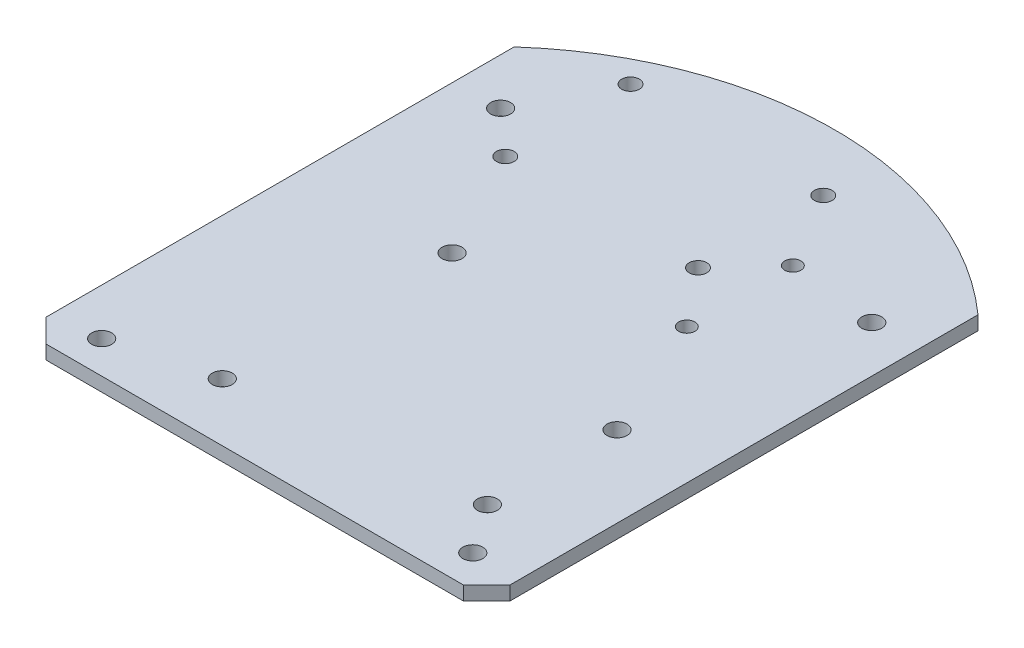
SolidWorks part; units mm, degrees
ref_plane "Front Plane" through (0, 0, 0) normal (0, 0, 1) x (1, 0, 0)
ref_plane "Top Plane" through (0, 0, 0) normal (0, 1, 0) x (1, 0, 0)
ref_plane "Right Plane" through (0, 0, 0) normal (1, 0, 0) x (0, 0, -1)
sketch "Sketch1" plane through (0, 0, 0) normal (0, 1, 0) x (1, 0, 0)
  line L1 (50, -50) -> (-50, -50)
  line L2 (50, -50) -> (50, 50)
  line L3 (50, 50) -> (-50, 50)
  line L4 (-50, -50) -> (-50, 50)
  line L5 (50, -50) -> (-50, 50) construction
  line L6 (50, 50) -> (-50, -50) construction
  point P0 (0, 0)
  dimension "D1" = 100
  dimension "D2" = 100
extrude "Boss-Extrude1" add sketch "Sketch1" along normal blind 3
sketch "Sketch2" plane through (0, 3, 0) normal (0, 1, 0) x (1, 0, 0)
  line L0 (0, -55) -> (0, 55) construction
  line L1 (-55, 0) -> (55, 0) construction
  circle A0 centre (-40, 43) radius 1.75
  dimension "D1" = 3.5
  dimension "D2" = 40
  dimension "D3" = 43
extrude "Cut-Extrude1" cut sketch "Sketch2" against normal through all
mirror "Mirror1" about plane through (0, 0, 0) normal (1, 0, 0) of "Cut-Extrude1"
mirror "Mirror2" about plane through (0, 0, 0) normal (0, 0, 1) of "Mirror1", "Cut-Extrude1"
chamfer "Chamfer1" distance 5 angle 45 4 edges at (-50, 1.5, 50) (50, 1.5, 50) (50, 1.5, -50) (-50, 1.5, -50)
sketch "Sketch6" plane through (0, 3, 0) normal (0, 1, 0) x (1, 0, 0)
  circle A4 centre (-18.23, 10.76) radius 1.75
  circle A5 centre (-19.5, -37.5) radius 1.75
  circle A6 centre (32.57, -32.42) radius 1.75
  circle A7 centre (32.57, -4.48) radius 1.75
  dimension "D1" = 3.5
  dimension "D2" = 3.5
  dimension "D3" = 3.5
  dimension "D4" = 3.5
sketch "Sketch7" plane through (0, 3, 0) normal (0, 1, 0) x (1, 0, 0)
  line L0 (-50, 45) -> (-50, 55.9017)
  line L1 (50, 45) -> (50, 55.9017)
  line L2 (45, 50) -> (-45, 50) construction
  arc A0 (-50, 55.9017) -> (50, 55.9017) centre (0, 0) cw
  dimension "D1" = 75
  dimension "D2" = 100
  dimension "D3" = 5.9017
sketch "Sketch8" plane through (0, 3, 0) normal (0, 1, 0) x (1, 0, 0)
  circle A0 centre (6.5, 61.5) radius 1.75 construction
  circle A1 centre (-30.5, 61.5) radius 1.75 construction
  circle A2 centre (6.5, 61.5) radius 1.75
  circle A3 centre (-30.5, 61.5) radius 1.75
  circle A5 centre (-30.5, 24.5) radius 1.75
  circle A6 centre (-30.5, 24.5) radius 1.75
  circle A7 centre (-30.5, 61.5) radius 1.75
  circle A8 centre (-30.5, 61.5) radius 1.75
  circle A9 centre (6.5, 61.5) radius 1.75
  circle A10 centre (6.5, 61.5) radius 1.75
  circle A11 centre (6.5, 24.5) radius 1.75
  circle A12 centre (6.5, 24.5) radius 1.75
  dimension "D1" = 0
  dimension "D2" = 0
  dimension "D3" = 0
  dimension "D4" = 0
sketch "Sketch9" plane through (0, 3, 0) normal (0, 1, 0) x (1, 0, 0)
  line L0 (50, 45) -> (50, 55.9017) construction
  line L1 (-50, 45) -> (-50, 55.9017) construction
  line L2 (50, 45) -> (50, 55.9017)
  line L3 (-50, 45) -> (-50, 55.9017)
  line L12 (-50, 45) -> (-50, -45)
  line L13 (-50, -45) -> (-45, -50)
  line L14 (-45, -50) -> (45, -50)
  line L15 (45, -50) -> (50, -45)
  line L16 (50, -45) -> (50, 45)
  line L17 (50, 45) -> (45, 50)
  line L18 (45, 50) -> (-45, 50)
  line L19 (-45, 50) -> (-50, 45)
  line L20 (-50, 45) -> (-50, -45)
  line L21 (-50, -45) -> (-45, -50)
  line L22 (-45, -50) -> (45, -50)
  line L23 (45, -50) -> (50, -45)
  line L24 (50, -45) -> (50, 45)
  line L25 (50, 45) -> (45, 50)
  line L26 (45, 50) -> (-45, 50)
  line L27 (-45, 50) -> (-50, 45)
  circle A0 centre (6.5, 24.5) radius 1.75 construction
  circle A1 centre (-30.5, 24.5) radius 1.75 construction
  circle A2 centre (6.5, 61.5) radius 1.75 construction
  circle A3 centre (-30.5, 61.5) radius 1.75 construction
  arc A4 (50, 55.9017) -> (-50, 55.9017) centre (0, 0) ccw construction
  circle A5 centre (6.5, 24.5) radius 1.75
  circle A6 centre (-30.5, 24.5) radius 1.75
  circle A7 centre (6.5, 61.5) radius 1.75
  circle A8 centre (-30.5, 61.5) radius 1.75
  arc A9 (50, 55.9017) -> (-50, 55.9017) centre (0, 0) ccw
  line M22 (50, 45) -> (45, 50)
  line M23 (45, 50) -> (-45, 50)
  line M24 (-45, 50) -> (-50, 45)
  dimension "D1" = 0
extrude "Boss-Extrude2" add sketch "Sketch9" against normal up to surface (3 mm away) contours L2 A9 L3 A7 A8 M24 M23 M22
extrude "Cut-Extrude4" cut sketch "Sketch6" against normal up to next contours A4 | A7 | A6 | A5
sketch "Sketch10" plane through (0, 3, 0) normal (0, 1, 0) x (1, 0, 0)
  line L0 (-30.5, 61.5) -> (11.05, 61.5) construction
  line L1 (-30.5, 61.5) -> (-30.5, 34.5) construction
  line L2 (-30.5, 34.5) -> (11.05, 34.5) construction
  line L3 (11.05, 61.5) -> (11.05, 34.5) construction
  circle A0 centre (-30.5, 61.5) radius 1.75 construction
  circle A1 centre (-30.5, 61.5) radius 1.75
  circle A2 centre (11.05, 61.5) radius 1.9
  circle A3 centre (-30.5, 61.5) radius 1.9
  circle A4 centre (11.05, 61.5) radius 1.75
  circle A5 centre (-30.5, 61.5) radius 1.5
  circle A6 centre (11.05, 61.5) radius 1.5
  circle A7 centre (-30.5, 34.5) radius 1.5
  circle A8 centre (-30.5, 34.5) radius 1.9
  circle A9 centre (11.05, 34.5) radius 1.5
  circle A10 centre (11.05, 34.5) radius 1.9
  circle A11 centre (40, 43) radius 1.75 construction
  circle A12 centre (-40, 43) radius 1.75 construction
  circle A13 centre (-18.23, 10.76) radius 1.75 construction
  circle A14 centre (32.57, -4.48) radius 1.75 construction
  circle A15 centre (40, -43) radius 1.75 construction
  circle A16 centre (32.57, -32.42) radius 1.75 construction
  circle A17 centre (-19.5, -37.5) radius 1.75 construction
  circle A18 centre (-40, -43) radius 1.75 construction
  circle A19 centre (40, 43) radius 1.75
  circle A20 centre (-40, 43) radius 1.75
  circle A21 centre (-18.23, 10.76) radius 1.75
  circle A22 centre (32.57, -4.48) radius 1.75
  circle A23 centre (40, -43) radius 1.75
  circle A24 centre (32.57, -32.42) radius 1.75
  circle A25 centre (-19.5, -37.5) radius 1.75
  circle A26 centre (-40, -43) radius 1.75
  circle A27 centre (-40, 43) radius 2.15
  circle A28 centre (-40, -43) radius 2.15
  circle A29 centre (-19.5, -37.5) radius 2.15
  circle A30 centre (32.57, -32.42) radius 2.15
  circle A31 centre (40, -43) radius 2.15
  circle A32 centre (32.57, -4.48) radius 2.15
  circle A33 centre (-18.23, 10.76) radius 2.15
  circle A34 centre (40, 43) radius 2.15
  point P3 (-29, 61.5)
  point P5 (9.15, 61.5)
  point P10 (9.3, 61.5)
  point P12 (9.55, 61.5)
  point P15 (-30.5, 60)
  point P17 (-30.5, 36)
  point P20 (9.55, 34.5)
  point P21 (-29, 34.5)
  circle M17 centre (-18.23, 10.76) radius 1.75
  circle M18 centre (32.57, -4.48) radius 1.75
  circle M19 centre (32.57, -32.42) radius 1.75
  circle M20 centre (-19.5, -37.5) radius 1.75
  circle M21 centre (-40, -43) radius 1.75
  circle M22 centre (40, -43) radius 1.75
  circle M23 centre (40, 43) radius 1.75
  circle M24 centre (-40, 43) radius 1.75
  circle M31 centre (-30.5, 61.5) radius 1.75
  dimension "D1" = 3.8
  dimension "D2" = 3.8
  dimension "D3" = 3.5
  dimension "D5" = 3
  dimension "D4" = 3
  dimension "D7" = 3
  dimension "D9" = 3.8
  dimension "D10" = 3
  dimension "D12" = 3.8
  dimension "D6" = 38.55
  dimension "D8" = 24
  dimension "D11" = 38.55
  dimension "D13" = 0.4
  dimension "D14" = 0.4
  dimension "D15" = 0.4
  dimension "D16" = 0.4
  dimension "D17" = 0.4
  dimension "D18" = 0.4
  dimension "D19" = 0.4
  dimension "D20" = 0.4
extrude "Cut-Extrude5" cut sketch "Sketch10" against normal up to surface (3 mm away) contours A27 M24 | M24 | A3 M31 | A5 M31 | A5 | A7 | A8 A7 | M17 | A33 M17 | M20 | A29 M20 | M21 | A28 M21 | M22 | A31 M22 | A30 M19 | M19 | M18 | A32 M18 | M23 | A34 M23 | A9 | A10 A9 | A6 | A4 A6 | A2 A4 up to face at (-18.23, 0, -9.01)
sketch "Sketch13" plane through (0, 3, 0) normal (0, 1, 0) x (1, 0, 0)
  line L0 (50, 55.9017) -> (50, -45)
  line L1 (50, 55.9017) -> (50, -45)
  line L2 (50, -45) -> (45, -50)
  line L3 (50, -45) -> (45, -50)
  line L4 (45, -50) -> (-45, -50)
  line L5 (45, -50) -> (-45, -50)
  line L6 (-45, -50) -> (-50, -45)
  line L7 (-45, -50) -> (-50, -45)
  line L8 (-50, -45) -> (-50, 55.9017)
  line L9 (-50, -45) -> (-50, 55.9017)
  line L10 (20.8552, 45.1291) -> (20.8552, 20.5475) construction
  circle A0 centre (40, -43) radius 2.15
  circle A1 centre (40, -43) radius 2.15
  circle A2 centre (-30.5, 61.5) radius 1.9
  circle A3 centre (-30.5, 61.5) radius 1.9
  arc A4 (50, 55.9017) -> (-50, 55.9017) centre (0, 0) ccw
  arc A5 (50, 55.9017) -> (-50, 55.9017) centre (0, 0) ccw
  circle A6 centre (-40, 43) radius 2.15
  circle A7 centre (-40, 43) radius 2.15
  circle A8 centre (-40, -43) radius 2.15
  circle A9 centre (-40, -43) radius 2.15
  circle A10 centre (11.05, 61.5) radius 1.9
  circle A11 centre (11.05, 61.5) radius 1.9
  circle A12 centre (40, 43) radius 2.15
  circle A13 centre (40, 43) radius 2.15
  circle A14 centre (32.57, -32.42) radius 2.15
  circle A15 centre (32.57, -32.42) radius 2.15
  circle A16 centre (-19.5, -37.5) radius 2.15
  circle A17 centre (-19.5, -37.5) radius 2.15
  circle A18 centre (-30.5, 34.5) radius 1.9
  circle A19 centre (-30.5, 34.5) radius 1.9
  circle A20 centre (-18.23, 10.76) radius 2.15
  circle A21 centre (-18.23, 10.76) radius 2.15
  circle A22 centre (32.57, -4.48) radius 2.15
  circle A23 centre (32.57, -4.48) radius 2.15
  circle A24 centre (11.05, 34.5) radius 1.9
  circle A25 centre (11.05, 34.5) radius 1.9
  circle A26 centre (20.8552, 45.1291) radius 1.75
  circle A27 centre (20.8341, 22.2974) radius 1.75
  circle A28 centre (-19.5, -37.5) radius 2.15 construction
  dimension "D1" = 3.5
  dimension "D2" = 3.5
  dimension "D3" = 40.3341
  dimension "D4" = 40.3552
  dimension "D5" = 59.7974
  dimension "D6" = 82.6291
extrude "Cut-Extrude6" cut sketch "Sketch13" against normal up to surface (3 mm away) contours A26 | A27 up to face at (32.57, 0, 6.63)
